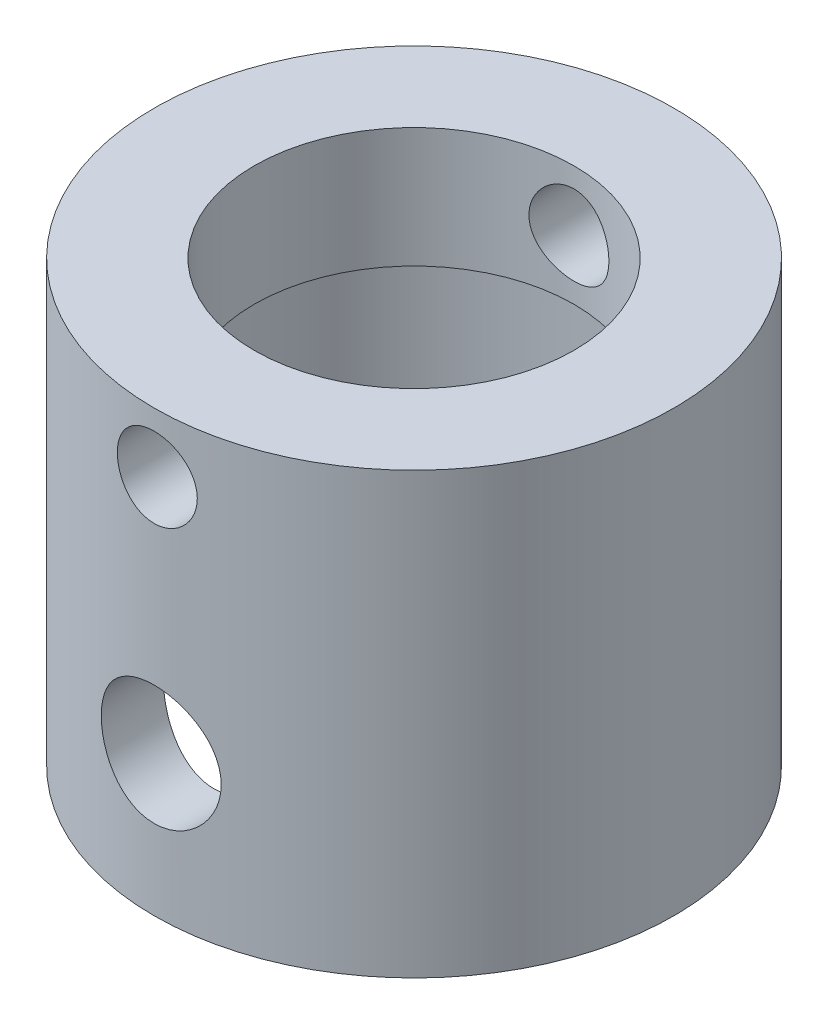
SolidWorks part; units mm, degrees
other "标注1"
sketch "草图5" plane through (-13, -16, 13) normal (-0.0443, -0.2155, 0.9755) x (0.999, 0, 0.0454)
ref_plane "前视基准面" through (0, 0, 0) normal (0, 0, 1) x (1, 0, 0)
ref_plane "上视基准面" through (0, 0, 0) normal (0, 1, 0) x (1, 0, 0)
ref_plane "右视基准面" through (0, 0, 0) normal (1, 0, 0) x (0, 0, -1)
sketch "草图1" plane through (0, 0, 0) normal (0, 1, 0) x (1, 0, 0)
  circle A0 centre (0, 0) radius 13
  dimension "D1" = 26
extrude "凸台-拉伸1" add sketch "草图1" along normal blind 22 from offset 16 offset against normal yes
sketch "草图2" plane through (0, 0, 0) normal (0, 1, 0) x (1, 0, 0)
  circle A0 centre (0, 0) radius 8
  dimension "D1" = 16
extrude "切除-拉伸1" cut sketch "草图2" along normal up to next
sketch "草图3" plane through (0, 0, 0) normal (0, 1, 0) x (1, 0, 0)
  circle A0 centre (0, 0) radius 10
  dimension "D1" = 20
extrude "切除-拉伸2" cut sketch "草图3" against normal up to next
sketch "草图4" plane through (0, 0, 0) normal (0, 0, 1) x (1, 0, 0)
  circle A0 centre (0, -9) radius 3
  circle A1 centre (0, 3) radius 2
  dimension "D2" = 4
  dimension "D4" = 6
  dimension "D1" = 3
  dimension "D3" = 9
extrude "切除-拉伸3" cut sketch "草图4" against normal through all both and the other way through all
